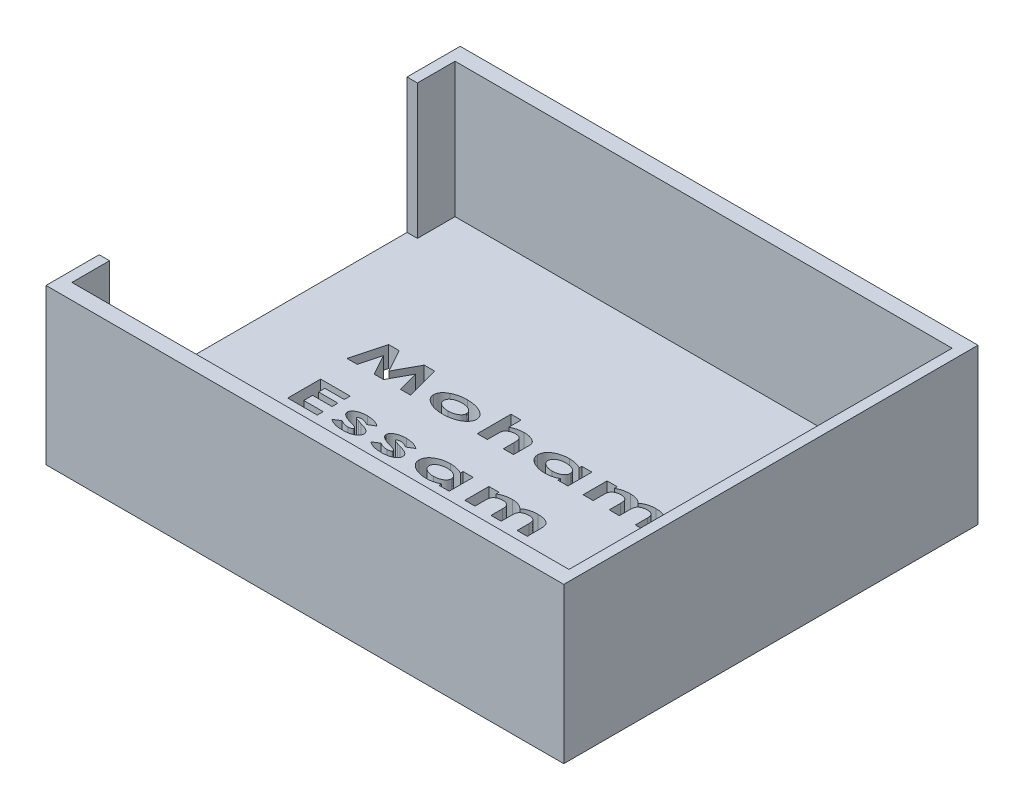
SolidWorks part; units mm, degrees
ref_plane "Front Plane" through (0, 0, 0) normal (0, 0, 1) x (1, 0, 0)
ref_plane "Top Plane" through (0, 0, 0) normal (0, 1, 0) x (1, 0, 0)
ref_plane "Right Plane" through (0, 0, 0) normal (1, 0, 0) x (0, 0, -1)
sketch "Sketch1" plane through (0, 0, 0) normal (0, 1, 0) x (1, 0, 0)
  line L1 (-25, 20) -> (25, 20)
  line L2 (-25, 20) -> (-25, -20)
  line L3 (-25, -20) -> (25, -20)
  line L4 (25, 20) -> (25, -20)
  line L5 (-25, 20) -> (25, -20) construction
  line L6 (-25, -20) -> (25, 20) construction
  point P0 (0, 0)
  dimension "D1" = 50
  dimension "D2" = 40
extrude "Boss-Extrude1" add sketch "Sketch1" along normal blind 15
sketch "Sketch2" plane through (0, 15, 0) normal (0, 1, 0) x (1, 0, 0)
  line L1 (-24, 18.5) -> (24, 18.5)
  line L2 (-24, 18.5) -> (-24, -18.5)
  line L3 (-24, -18.5) -> (24, -18.5)
  line L4 (24, 18.5) -> (24, -18.5)
  line L5 (-24, 18.5) -> (24, -18.5) construction
  line L6 (-24, -18.5) -> (24, 18.5) construction
  point P0 (0, 0)
  dimension "D1" = 48
  dimension "D2" = 37
extrude "Cut-Extrude1" cut sketch "Sketch2" against normal blind 13
sketch "Sketch3" plane through (-25, 0, 0) normal (-1, 0, 0) x (0, 0, 1)
  line L2 (-14.8661, 2) -> (-14.8661, 15)
  line L3 (-20, 15) -> (20, 15) construction
  line L5 (14.8661, 2) -> (14.8661, 15)
  line L6 (0, 0) -> (0, 2) construction
  line L7 (14.8661, 2) -> (-14.8661, 2)
  line L8 (14.8661, 15) -> (-14.8661, 15)
  point P1 (14.8661, 0)
  point P3 (14.8661, 2.2852)
  point P10 (-15, 0)
  point P12 (0, 0)
  point P15 (0, 2)
  point P16 (-14.9013, 1.7175)
  dimension "D2" = 2
extrude "Cut-Extrude2" cut sketch "Sketch3" against normal blind 12
sketch "Sketch4" plane through (0, 2, 0) normal (0, 1, 0) x (1, 0, 0)
  text T0 "<b>Mohamed </b>\r\n<b>Essam</b>" font "Century Gothic" height 3.175
extrude "Cut-Extrude3" cut sketch "Sketch4" against normal blind 12
